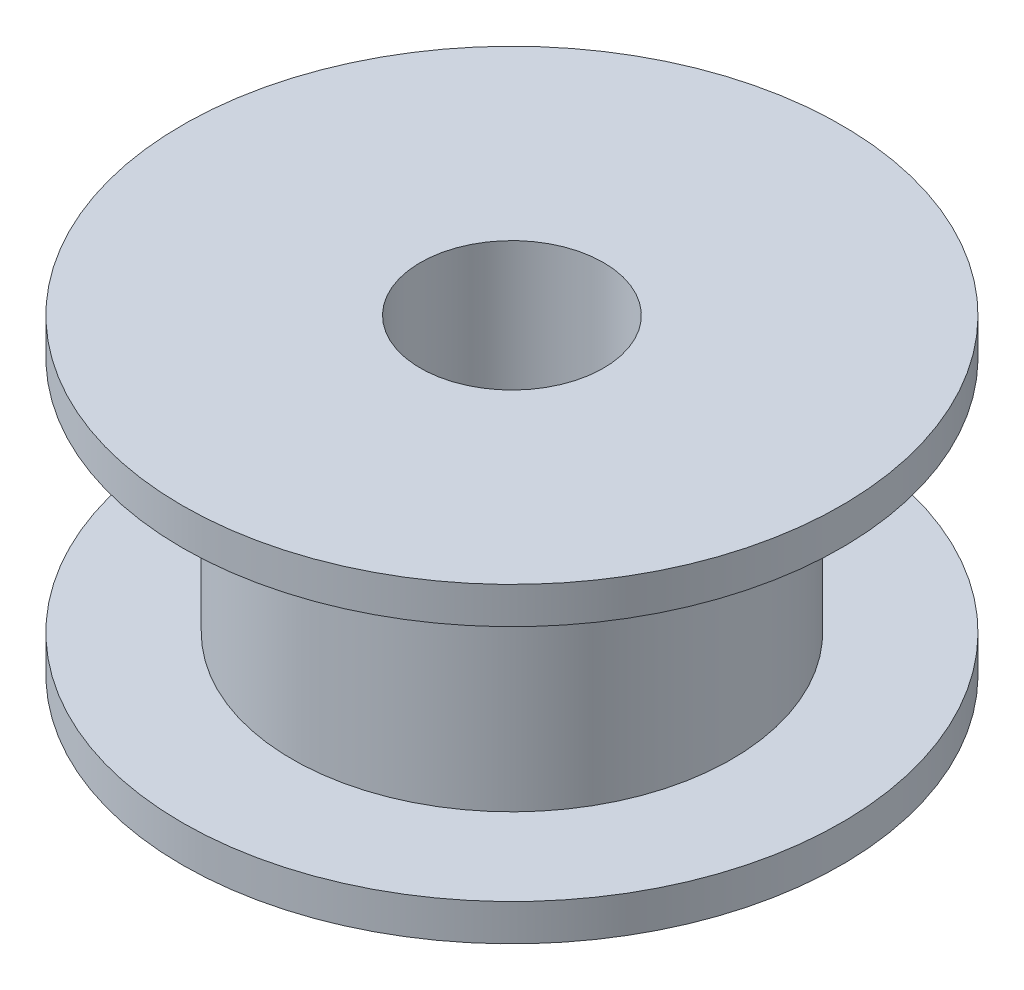
SolidWorks part; units mm, degrees
ref_plane "前视基准面" through (0, 0, 0) normal (0, 0, 1) x (1, 0, 0)
ref_plane "上视基准面" through (0, 0, 0) normal (0, 1, 0) x (1, 0, 0)
ref_plane "右视基准面" through (0, 0, 0) normal (1, 0, 0) x (0, 0, -1)
sketch "草图1" plane through (0, 0, 0) normal (0, 1, 0) x (1, 0, 0)
  circle A0 centre (0, 0) radius 9
  dimension "D1" = 18
extrude "凸台-拉伸1" add sketch "草图1" along normal blind 1
sketch "草图2" plane through (0, 1, 0) normal (0, 1, 0) x (1, 0, 0)
  circle A0 centre (0, 0) radius 6
  dimension "D1" = 12
extrude "凸台-拉伸2" add sketch "草图2" along normal blind 6.5
sketch "草图5" plane through (0, 7.5, 0) normal (0, 1, 0) x (1, 0, 0)
  circle A0 centre (0, 0) radius 9
  dimension "D1" = 18
extrude "凸台-拉伸3" add sketch "草图5" along normal blind 1
sketch "草图6" plane through (0, 0, 0) normal (0, -1, 0) x (1, 0, 0)
  circle A0 centre (0, 0) radius 2.5
  dimension "D1" = 5
extrude "切除-拉伸1" cut sketch "草图6" against normal through all
